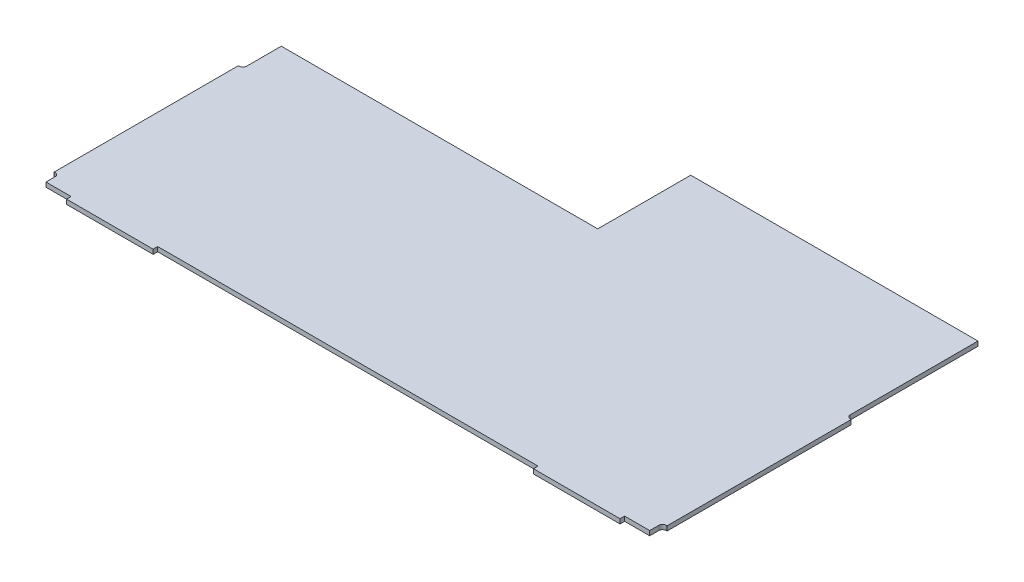
SolidWorks part; units mm, degrees
material "6061-T6 (SS)"
ref_plane "X-Y Datum" through (0, 0, 0) normal (0, 0, 1) x (1, 0, 0)
ref_plane "X-Z Datum" through (0, 0, 0) normal (0, 1, 0) x (1, 0, 0)
ref_plane "Y-Z Datum" through (0, 0, 0) normal (1, 0, 0) x (0, 0, -1)
sketch "Sketch1" plane through (0, 0, 0) normal (0, 1, 0) x (1, 0, 0)
  line L0 (197.0053, -26.67) -> (197.0053, -163.83)
  line L1 (197.0053, -163.83) -> (176.3678, -163.83)
  line L2 (-229.7147, -154.94) -> (-229.7147, -26.67)
  line L3 (-226.5397, 0) -> (-6.1947, 0)
  line L4 (-6.1947, 0) -> (-6.1947, 64.77)
  line L5 (-6.1947, 64.77) -> (193.8303, 64.77)
  line L6 (176.3678, -163.83) -> (176.3678, -167.005)
  line L7 (176.3678, -167.005) -> (116.0428, -167.005)
  line L8 (116.0428, -167.005) -> (116.0428, -163.83)
  line L9 (193.8303, 64.77) -> (193.8303, -24.13)
  line L10 (0, -43.0151) -> (0, 43.0151) construction
  line L14 (116.0428, -163.83) -> (-116.0428, -163.83)
  line L15 (-209.0772, -163.83) -> (-226.5397, -163.83)
  line L16 (196.3703, -26.67) -> (197.0053, -26.67)
  line L17 (-226.5397, 0) -> (-226.5397, -24.13)
  line L18 (-229.0797, -26.67) -> (-229.7147, -26.67)
  line L19 (-229.7147, -154.94) -> (-229.0797, -154.94)
  line L20 (-226.5397, -157.48) -> (-226.5397, -163.83)
  line L21 (-16.3547, -163.83) -> (-16.3547, 76.5136) construction
  line L22 (-148.7522, -167.005) -> (-148.7522, -163.83)
  line L23 (-209.0772, -167.005) -> (-148.7522, -167.005)
  line L24 (-209.0772, -163.83) -> (-209.0772, -167.005)
  line L25 (-148.7522, -163.83) -> (-116.0428, -163.83)
  line L26 (-229.7147, -17.78) -> (197.0053, -17.78) construction
  arc A0 (193.8303, -24.13) -> (196.3703, -26.67) centre (196.3703, -24.13) ccw
  arc A1 (-226.5397, -24.13) -> (-229.0797, -26.67) centre (-229.0797, -24.13) cw
  arc A2 (-229.0797, -154.94) -> (-226.5397, -157.48) centre (-229.0797, -157.48) cw
  point P9 (146.2053, -167.005)
  point P22 (193.8303, -26.67)
  point P28 (-226.5397, -26.67)
  point P35 (-226.5397, -154.94)
  dimension "D1" = 2.54
  dimension "D13" = 2.54
  dimension "D16" = 2.54
  dimension "D2" = 213.36
  dimension "D3" = 3.175
  dimension "D4" = 60.325
  dimension "D5" = 50.8
  dimension "D6" = 203.2
  dimension "D7" = 426.72
  dimension "D8" = 8.89
  dimension "D9" = 3.175
  dimension "D10" = 228.6
  dimension "D11" = 8.89
  dimension "D12" = 3.175
  dimension "D14" = 8.89
  dimension "D15" = 3.175
  dimension "D17" = 64.77
  dimension "D18" = 146.05
extrude "Boss-Extrude1" add sketch "Sketch1" along normal blind 3.175
sketch "Sketch2" plane through (0, 3.175, 0) normal (0, 1, 0) x (1, 0, 0)
  line L1 (197.0053, -163.83) -> (193.8303, -163.83)
  line L2 (197.0053, -163.83) -> (197.0053, -154.94)
  line L3 (197.0053, -154.94) -> (196.3703, -154.94)
  line L4 (193.8303, -163.83) -> (193.8303, -157.48)
  arc A0 (196.3703, -154.94) -> (193.8303, -157.48) centre (196.3703, -157.48) ccw
  dimension "D3" = 2.54
  dimension "D1" = 3.175
  dimension "D2" = 8.89
extrude "Cut-Extrude1" cut sketch "Sketch2" against normal through all both and the other way through all
